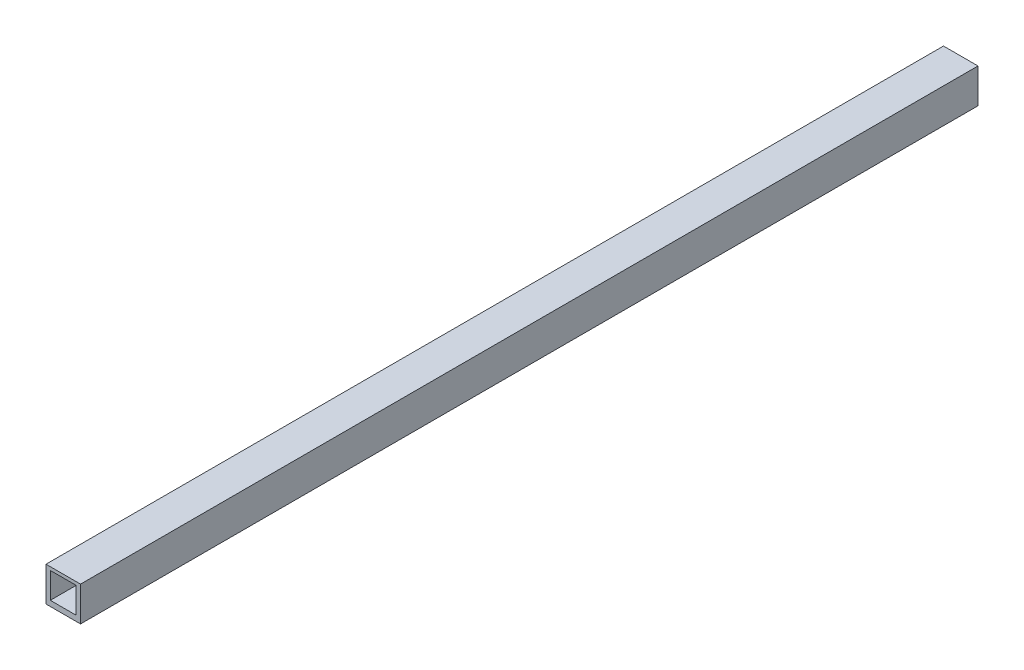
SolidWorks part; units mm, degrees
ref_plane "Front Plane" through (0, 0, 0) normal (0, 0, 1) x (1, 0, 0)
ref_plane "Top Plane" through (0, 0, 0) normal (0, 1, 0) x (1, 0, 0)
ref_plane "Right Plane" through (0, 0, 0) normal (1, 0, 0) x (0, 0, -1)
sketch "Sketch1" plane through (0, 0, 0) normal (0, 0, 1) x (1, 0, 0)
  line L1 (-12.7, -13.4893) -> (12.7, -13.4893)
  line L2 (-12.7, -13.4893) -> (-12.7, 11.9107)
  line L3 (-12.7, 11.9107) -> (12.7, 11.9107)
  line L4 (12.7, -13.4893) -> (12.7, 11.9107)
  line L5 (-12.7, -13.4893) -> (12.7, 11.9107) construction
  line L6 (-12.7, 11.9107) -> (12.7, -13.4893) construction
  point P0 (0, -0.7893)
  dimension "D1" = 25.4
  dimension "D2" = 25.4
extrude "Boss-Extrude1" add sketch "Sketch1" along normal blind 660.4
sketch "Sketch2" plane through (0, 0, 660.4) normal (0, 0, 1) x (1, 0, 0)
  line L1 (-9.525, -9.525) -> (9.525, -9.525)
  line L2 (-9.525, -9.525) -> (-9.525, 9.525)
  line L3 (-9.525, 9.525) -> (9.525, 9.525)
  line L4 (9.525, -9.525) -> (9.525, 9.525)
  line L5 (-9.525, -9.525) -> (9.525, 9.525) construction
  line L6 (-9.525, 9.525) -> (9.525, -9.525) construction
  point P0 (0, 0)
  dimension "D1" = 19.05
  dimension "D2" = 19.05
extrude "Cut-Extrude1" cut sketch "Sketch2" against normal up to surface (660.4 mm away) up to face at (0, -0.7893, 0)
